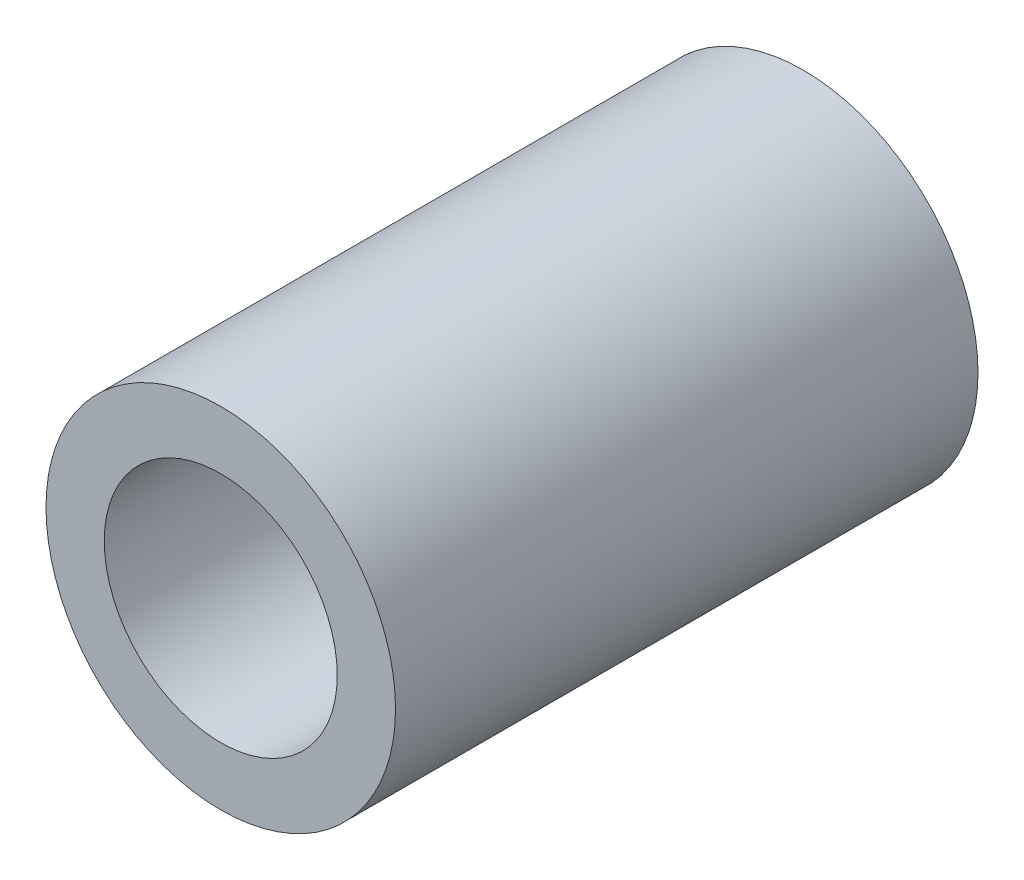
SolidWorks part; units mm, degrees
ref_plane "Plano frontal" through (0, 0, 0) normal (0, 0, 1) x (1, 0, 0)
ref_plane "Plano superior" through (0, 0, 0) normal (0, 1, 0) x (1, 0, 0)
ref_plane "Plano direito" through (0, 0, 0) normal (1, 0, 0) x (0, 0, -1)
sketch "Esboço1" plane through (0, 0, 0) normal (0, 0, 1) x (1, 0, 0)
  circle A0 centre (0, 0) radius 2
  circle A1 centre (0, 0) radius 3
  dimension "D1" = 4
  dimension "D2" = 6
extrude "Ressalto-extrusão1" add sketch "Esboço1" along normal blind 10
